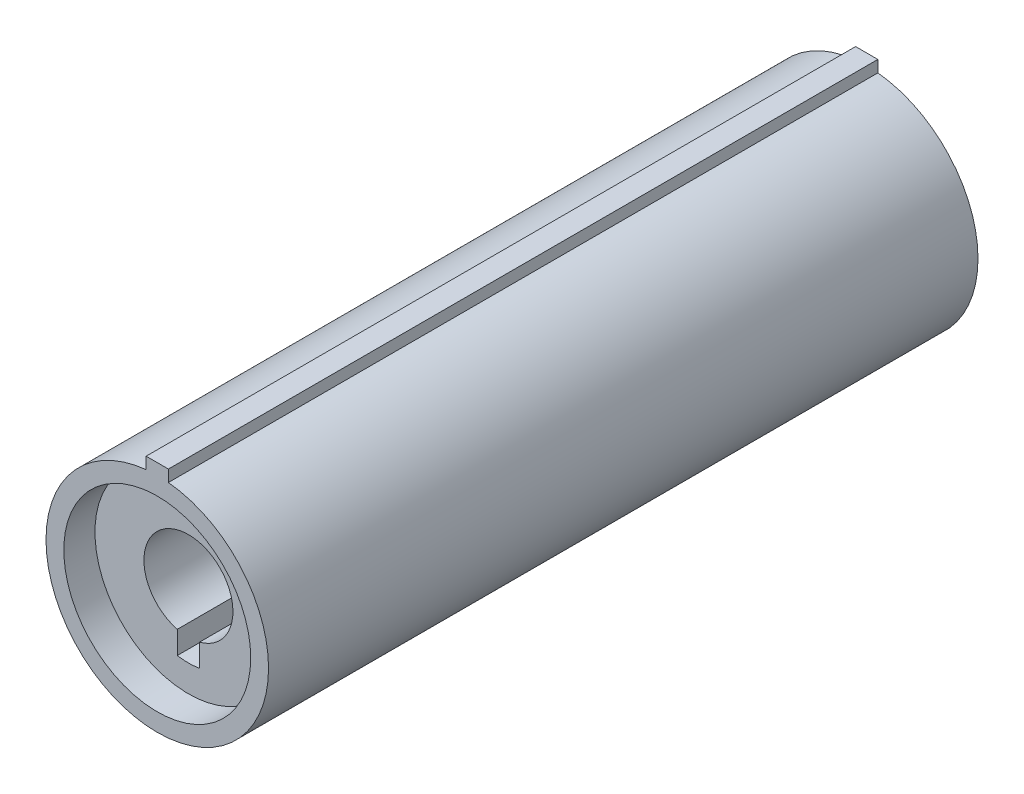
SolidWorks part; units mm, degrees
ref_plane "Front Plane" through (0, 0, 0) normal (0, 0, 1) x (1, 0, 0)
ref_plane "Top Plane" through (0, 0, 0) normal (0, 1, 0) x (1, 0, 0)
ref_plane "Right Plane" through (0, 0, 0) normal (1, 0, 0) x (0, 0, -1)
sketch "Sketch1" plane through (0, 0, 0) normal (0, 0, 1) x (1, 0, 0)
  line L3 (-2.5, 24.8747) -> (-2.5, 27.5)
  line L4 (-2.5, 27.5) -> (2.5, 27.5)
  line L5 (2.5, 27.5) -> (2.5, 24.8747)
  line L8 (-2.5, -9.6825) -> (-2.5, -25)
  line L9 (-2.5, -25) -> (2.5, -25)
  line L10 (2.5, -9.6825) -> (2.5, -25)
  arc A0 (-2.5, 24.8747) -> (2.5, 24.8747) centre (0, 0) ccw
  arc A1 (2.5, -9.6825) -> (-2.5, -9.6825) centre (0, 0) ccw
  point P12 (0, 27.5)
  point P13 (0, -25)
  dimension "D1" = 20
  dimension "D2" = 50
  dimension "D3" = 5
  dimension "D5" = 27.5
extrude "Boss-Extrude1" add sketch "Sketch1" along normal blind 152.4 contours A1 L10 A0 L5 L4 L3 L8
sketch "Sketch3" plane through (0, 0, 152.4) normal (0, 0, 1) x (1, 0, 0)
  line L6 (-2.5, 27.5) -> (2.5, 27.5)
  line L8 (-2.5, 27.5) -> (-2.5, 24.8747)
  line L10 (2.5, 27.5) -> (2.5, 24.8747)
  circle A0 centre (0, 0) radius 21
  arc A1 (-2.5, -24.8747) -> (2.5, 24.8747) centre (0, 0) ccw
  arc A3 (-2.5, 24.8747) -> (-2.5, -24.8747) centre (0, 0) ccw
  arc A4 (-2.5, 24.8747) -> (-2.5, -24.8747) centre (0, 0) ccw construction
  dimension "D1" = 42
extrude "Boss-Extrude2" add sketch "Sketch3" along normal blind 7
sketch "Sketch4" plane through (0, 0, 152.4) normal (0, 0, 1) x (1, 0, 0)
  line L0 (2.5, -9.6825) -> (2.5, -20.8507) construction
  line L2 (-2.5, -14.7902) -> (-2.5, -24.8747)
  line L3 (2.5, -24.8747) -> (2.5, -14.7902)
  line L4 (-2.5, -9.6825) -> (-2.5, -20.8507) construction
  arc A0 (-2.5, -14.7902) -> (2.5, -14.7902) centre (0, 0) ccw
  arc A1 (-2.5, -9.6825) -> (2.5, -9.6825) centre (0, 0) ccw construction
  arc A2 (-2.5, -24.8747) -> (2.5, -24.8747) centre (0, 0) ccw
  arc A3 (-2.5, 24.8747) -> (2.5, 24.8747) centre (0, 0) ccw construction
  point P8 (0, -10)
  point P12 (0, -15)
  dimension "D1" = 5
extrude "Boss-Extrude3" add sketch "Sketch4" against normal up to surface (152.4 mm away) up to face at (0, 6.9147, 0)
